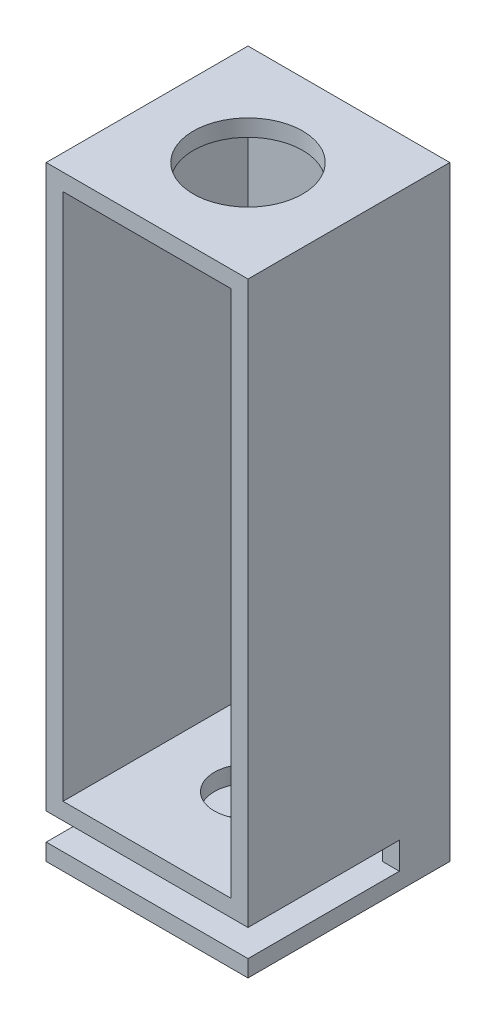
SolidWorks part; units mm, degrees
ref_plane "Alzado" through (0, 0, 0) normal (0, 0, 1) x (1, 0, 0)
ref_plane "Planta" through (0, 0, 0) normal (0, 1, 0) x (1, 0, 0)
ref_plane "Vista lateral" through (0, 0, 0) normal (1, 0, 0) x (0, 0, -1)
sketch "Croquis1" plane through (0, 0, 0) normal (0, 1, 0) x (1, 0, 0)
  line L1 (-6, 6) -> (6, 6)
  line L2 (-6, 6) -> (-6, -6)
  line L3 (-6, -6) -> (6, -6)
  line L4 (6, 6) -> (6, -6)
  line L5 (-6, 6) -> (6, -6) construction
  line L6 (-6, -6) -> (6, 6) construction
  point P0 (0, 0)
  dimension "D1" = 12
  dimension "D2" = 12
extrude "Saliente-Extruir1" add sketch "Croquis1" along normal blind 36
shell "Vaciado1" thickness 1
sketch "Croquis2" plane through (0, 36, 0) normal (0, 1, 0) x (1, 0, 0)
  circle A0 centre (0, 0) radius 3.25
  dimension "D1" = 6.5
extrude "Cortar-Extruir1" cut sketch "Croquis2" against normal blind 3 and the other way through all
sketch "Croquis3" plane through (0, 0, 6) normal (0, 0, 1) x (1, 0, 0)
  line L1 (-6.7727, 1) -> (6.8802, 1)
  line L2 (-6.7727, 1) -> (-6.7727, 2.6)
  line L3 (-6.7727, 2.6) -> (6.8802, 2.6)
  line L4 (6.8802, 1) -> (6.8802, 2.6)
  line L5 (-6, 0) -> (6, 0) construction
  dimension "D1" = 1.6
  dimension "D2" = 1
extrude "Cortar-Extruir2" cut sketch "Croquis3" against normal blind 9
sketch "Croquis4" plane through (0, 0, 6) normal (0, 0, 1) x (1, 0, 0)
  line L0 (5, 35) -> (5, 2.6) construction
  line L1 (-5, 2.6) -> (5, 2.6)
  line L2 (-5, 2.6) -> (-5, 3.6)
  line L3 (-5, 3.6) -> (5, 3.6)
  line L4 (5, 2.6) -> (5, 3.6)
  dimension "D1" = 1
extrude "Saliente-Extruir2" add sketch "Croquis4" against normal up to surface (11 mm away) up to face at (0, 18, -5)
sketch "Croquis5" plane through (0, 36, 0) normal (0, 1, 0) x (1, 0, 0)
  circle A0 centre (0, 0) radius 2
  dimension "D1" = 4
extrude "Cortar-Extruir3" cut sketch "Croquis5" against normal through all
